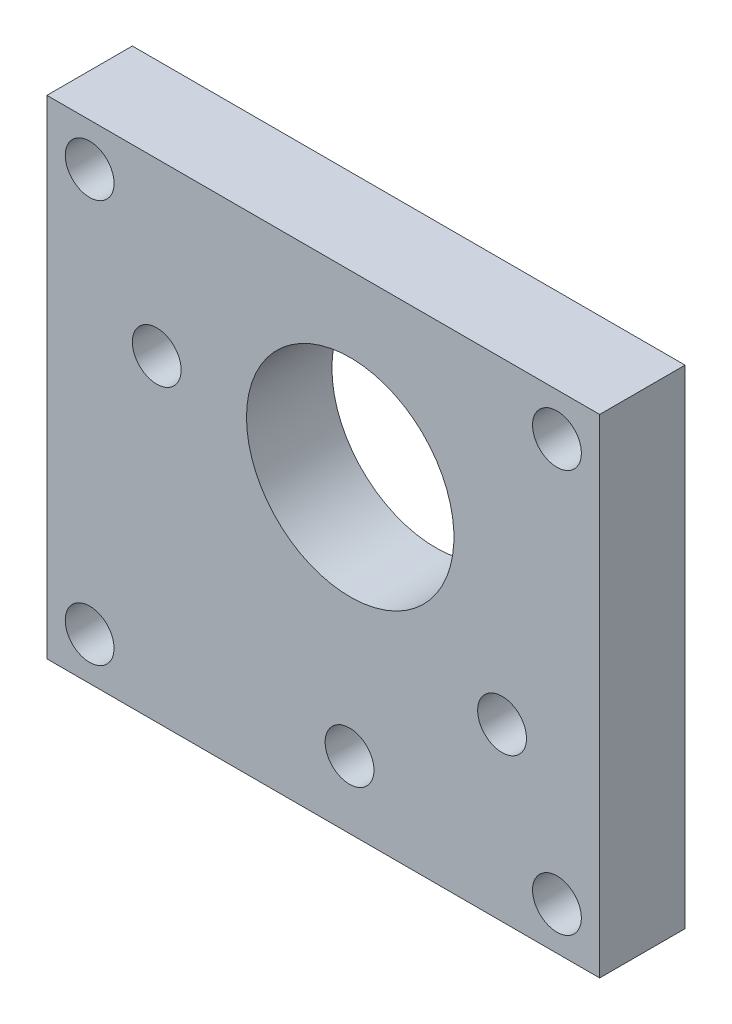
SolidWorks part; units mm, degrees
ref_plane "Plan de face" through (0, 0, 0) normal (0, 0, 1) x (1, 0, 0)
ref_plane "Plan de dessus" through (0, 0, 0) normal (0, 1, 0) x (1, 0, 0)
ref_plane "Plan de droite" through (0, 0, 0) normal (1, 0, 0) x (0, 0, -1)
sketch "Esquisse1" plane through (0, 0, 0) normal (0, 0, 1) x (1, 0, 0)
  line L1 (-19.1726, 20.5454) -> (26.1274, 20.5454)
  line L2 (-19.1726, 20.5454) -> (-19.1726, -19.4546)
  line L3 (-19.1726, -19.4546) -> (26.1274, -19.4546)
  line L4 (26.1274, 20.5454) -> (26.1274, -19.4546)
  dimension "D1" = 45.3
  dimension "D2" = 40
extrude "Boss.-Extru.1" add sketch "Esquisse1" against normal blind 7
hole_wizard "Chambrage pour vis à six pans creux M42" positions "Esquisse4" profile "Esquisse5" counterbore size "M4" standard "ISO" end condition up to next
sketch "Esquisse4" plane through (0, 0, -7) normal (0, 0, -1) x (-1, 0, 0)
  line L0 (-26.1274, 20.5454) -> (19.1726, 20.5454) construction
  line L1 (-26.1274, -19.4546) -> (-26.1274, 20.5454) construction
  line L2 (19.1726, 20.5454) -> (19.1726, -19.4546) construction
  line L3 (19.1726, -19.4546) -> (-26.1274, -19.4546) construction
  point P0 (-22.6274, 17.0454)
  point P7 (15.6726, 17.0454)
  point P12 (15.6726, -15.9546)
  point P17 (-22.6274, -15.9546)
  dimension "D1" = 3.5
  dimension "D2" = 3.5
  dimension "D3" = 3.5
  dimension "D4" = 3.5
sketch "Esquisse5" plane through (22.6274, 17.0454, -7) normal (1, 0, 0) x (0, 1, 0)
  line L0 (0, 0) -> (0, 7)
  line L1 (0, 7) -> (2, 7)
  line L3 (2, 7) -> (2, 3)
  line L4 (2, 3) -> (3, 3)
  line L5 (3, 3) -> (3, 0)
  line L7 (3, 0) -> (0, 0)
  line L11 (0, -6.35) -> (0, 107.95) construction
  dimension "Diamètre du perçage jusqu'au prochain" = 4
  dimension "Profondeur du perçage jusqu'au prochain" = 7
  dimension "Diamètre du chambrage" = 6
  dimension "Profondeur du chambrage" = 3
sketch "Esquisse8" plane through (0, 0, -7) normal (0, 0, -1) x (-1, 0, 0)
  circle A0 centre (-5.683, 5.8664) radius 8.5
  dimension "D1" = 17
extrude "Enlèv. mat.-Extru.1" cut sketch "Esquisse8" against normal blind 7 contours A0
hole_wizard "Chambrage pour vis à six pans creux M43" positions "Esquisse9" profile "Esquisse10" counterbore size "M4" standard "ISO" end condition up to next
sketch "Esquisse9" plane through (0, 0, -7) normal (0, 0, -1) x (-1, 0, 0)
  line L0 (-26.1274, -19.4546) -> (-26.1274, 20.5454) construction
  line L1 (19.1726, -19.4546) -> (-26.1274, -19.4546) construction
  line L2 (19.1726, 20.5454) -> (19.1726, -19.4546) construction
  line L3 (-26.1274, 20.5454) -> (19.1726, 20.5454) construction
  point P0 (-5.6274, -13.9546)
  point P2 (-18.1274, -5.4546)
  point P4 (10.1726, 6.5454)
  dimension "D1" = 20.5
  dimension "D2" = 5.5
  dimension "D3" = 8
  dimension "D4" = 14
  dimension "D5" = 9
  dimension "D6" = 14
sketch "Esquisse10" plane through (5.6274, -13.9546, -7) normal (1, 0, 0) x (0, 1, 0)
  line L0 (0, 0) -> (0, 7)
  line L1 (0, 7) -> (2, 7)
  line L3 (2, 7) -> (2, 3)
  line L4 (2, 3) -> (3, 3)
  line L5 (3, 3) -> (3, 0)
  line L7 (3, 0) -> (0, 0)
  line L11 (0, -6.35) -> (0, 107.95) construction
  dimension "Diamètre du perçage jusqu'au prochain" = 4
  dimension "Profondeur du perçage jusqu'au prochain" = 7
  dimension "Diamètre du chambrage" = 6
  dimension "Profondeur du chambrage" = 3
